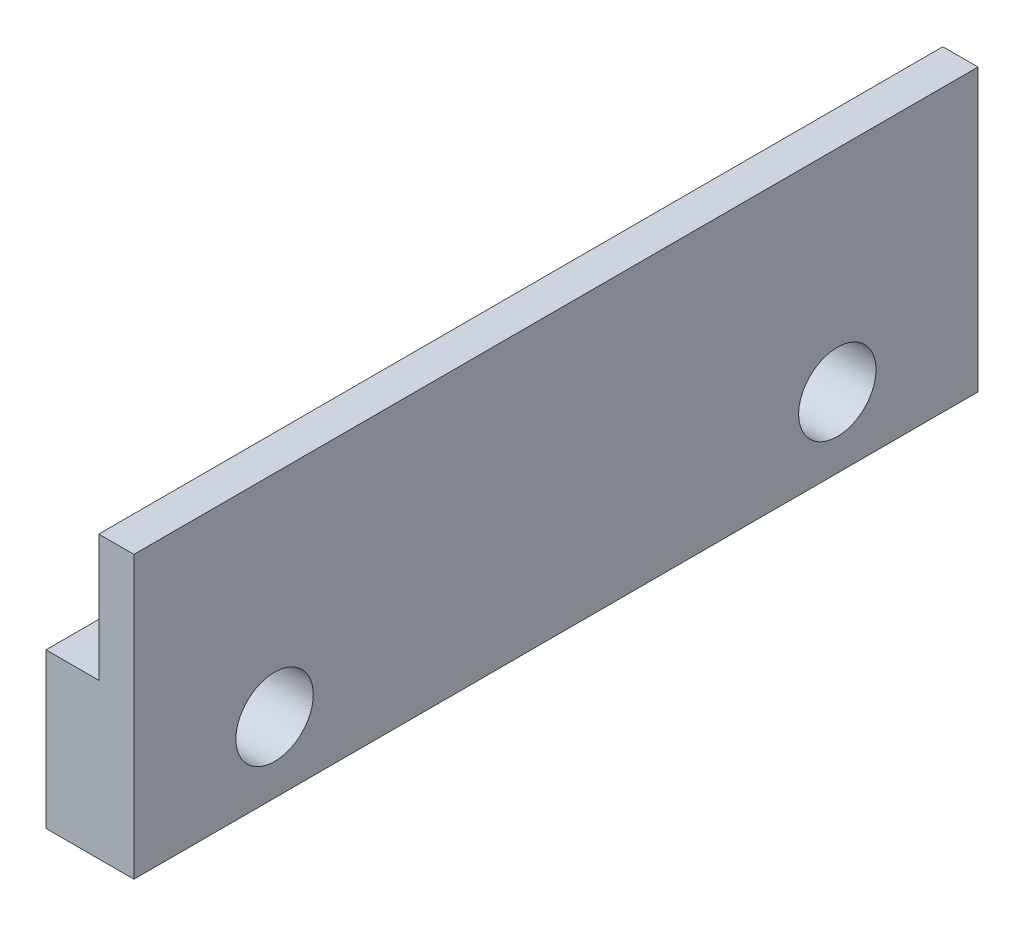
SolidWorks part; units mm, degrees
ref_plane "Front Plane" through (0, 0, 0) normal (0, 0, 1) x (1, 0, 0)
ref_plane "Top Plane" through (0, 0, 0) normal (0, 1, 0) x (1, 0, 0)
ref_plane "Right Plane" through (0, 0, 0) normal (1, 0, 0) x (0, 0, -1)
sketch "Sketch1" plane through (0, 0, 0) normal (0, 0, 1) x (1, 0, 0)
  line L0 (0, 17.2641) -> (0, -5.5959)
  line L1 (0, 17.2641) -> (6.35, 17.2641)
  line L2 (-9.525, -5.5959) -> (-9.525, -33.5359)
  line L3 (-9.525, -33.5359) -> (6.35, -33.5359)
  line L4 (6.35, 17.2641) -> (6.35, -33.5359)
  line L5 (0, -5.5959) -> (-9.525, -5.5959)
  dimension "D1" = 9.525
  dimension "D2" = 50.8
  dimension "D3" = 22.86
  dimension "D4" = 15.875
extrude "Boss-Extrude1" add sketch "Sketch1" along normal blind 152.4
sketch "Sketch2" plane through (6.35, 0, 0) normal (1, 0, 0) x (0, 0, -1)
  line L0 (-76.2, 17.2641) -> (-76.2, -33.5359) construction
  line L1 (-152.4, 17.2641) -> (0, 17.2641) construction
  line L2 (-152.4, -33.5359) -> (0, -33.5359) construction
  line L3 (-152.4, -33.5359) -> (-152.4, 17.2641) construction
  circle A0 centre (-127, -20.8359) radius 6.985
  circle A1 centre (-25.4, -20.8359) radius 6.985
  dimension "D1" = 12.7
  dimension "D2" = 25.4
extrude "Cut-Extrude1" cut sketch "Sketch2" against normal blind 15.875
